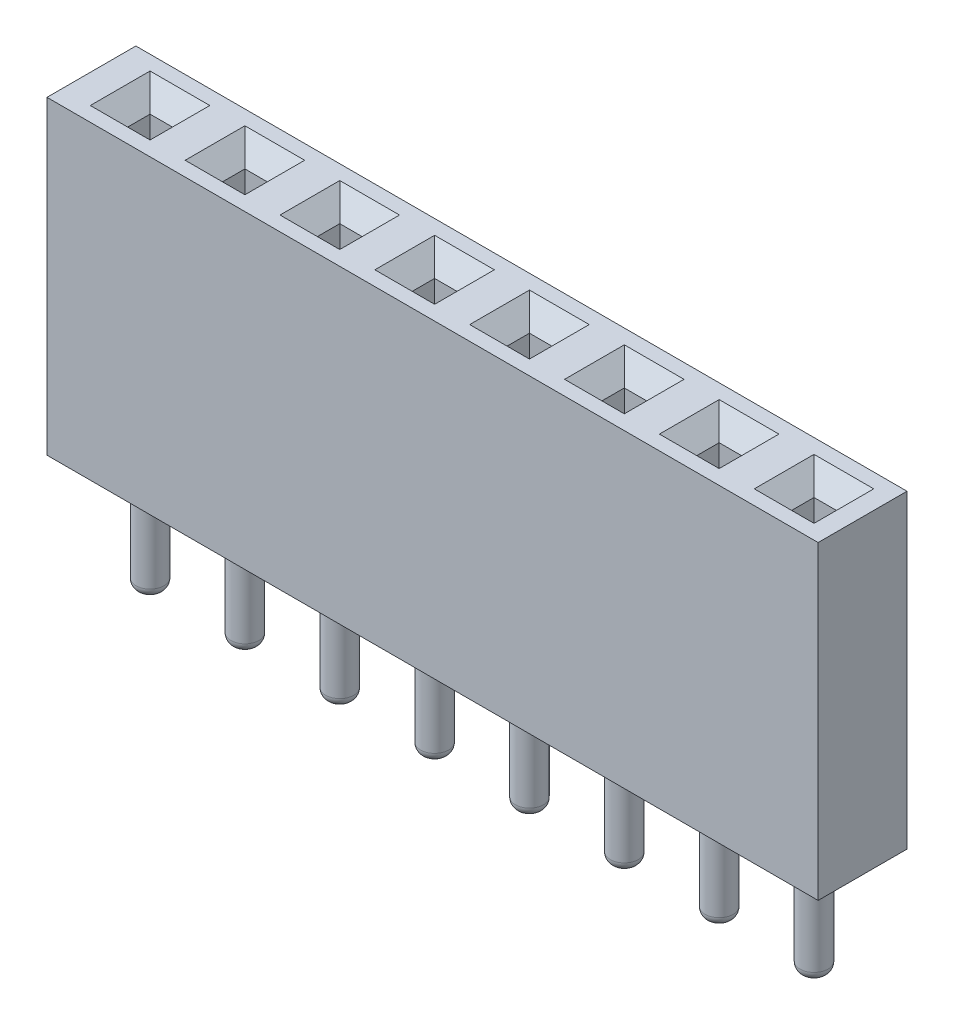
SolidWorks part; units mm, degrees
ref_plane "Front Plane" through (0, 0, 0) normal (0, 0, 1) x (1, 0, 0)
ref_plane "Top Plane" through (0, 0, 0) normal (0, 1, 0) x (1, 0, 0)
ref_plane "Right Plane" through (0, 0, 0) normal (1, 0, 0) x (0, 0, -1)
sketch "Sketch1" plane through (0, 0, 0) normal (0, 1, 0) x (1, 0, 0)
  line L1 (-10.325, -1.19) -> (10.325, -1.19)
  line L2 (-10.325, -1.19) -> (-10.325, 1.19)
  line L3 (-10.325, 1.19) -> (10.325, 1.19)
  line L4 (10.325, -1.19) -> (10.325, 1.19)
  line L5 (-10.325, -1.19) -> (10.325, 1.19) construction
  line L6 (-10.325, 1.19) -> (10.325, -1.19) construction
  point P0 (0, 0)
  dimension "D1" = 2.38
  dimension "D2" = 20.65
extrude "Boss-Extrude1" add sketch "Sketch1" along normal blind 8.3
sketch "Sketch2" plane through (0, 8.3, 0) normal (0, 1, 0) x (1, 0, 0)
  line L0 (-10.325, 0) -> (10.325, 0) construction
  line L1 (-10.325, 1.19) -> (-10.325, -1.19) construction
  line L2 (10.325, -1.19) -> (10.325, 1.19) construction
  line L4 (-9.055, -0.3) -> (-8.455, -0.3)
  line L5 (-9.055, -0.3) -> (-9.055, 0.3)
  line L6 (-9.055, 0.3) -> (-8.455, 0.3)
  line L7 (-8.455, -0.3) -> (-8.455, 0.3)
  line L8 (-9.055, -0.3) -> (-8.455, 0.3) construction
  line L9 (-9.055, 0.3) -> (-8.455, -0.3) construction
  point P6 (-8.755, 0)
  dimension "D1" = 0.6
  dimension "D2" = 0.6
  dimension "D3" = 1.27
extrude "Cut-Extrude1" cut sketch "Sketch2" against normal blind 8.3
chamfer "Chamfer1" distance 0.5 angle 45 4 edges at (-9.055, 8.3, 0) (-8.755, 8.3, 0.3) (-8.455, 8.3, 0) (-8.755, 8.3, -0.3)
sketch "Sketch3" plane through (0, 0, 0) normal (0, -1, 0) x (1, 0, 0)
  line L0 (-9.055, 0.3) -> (-8.455, 0.3) construction
  line L1 (-8.455, 0.3) -> (-8.455, -0.3) construction
  line L2 (-8.455, -0.3) -> (-9.055, -0.3) construction
  line L3 (-9.055, -0.3) -> (-9.055, 0.3) construction
  line L4 (-9.055, 0.3) -> (-8.455, 0.3) construction
  line L5 (-8.455, 0.3) -> (-8.455, -0.3) construction
  line L6 (-8.455, -0.3) -> (-9.055, -0.3) construction
  line L7 (-9.055, -0.3) -> (-9.055, 0.3) construction
  circle A0 centre (-8.755, 0) radius 0.375
  dimension "D1" = 0.75
extrude "Boss-Extrude2" add sketch "Sketch3" along normal blind 2.9
sketch "Sketch4" plane through (0, 0, 0) normal (0, 1, 0) x (1, 0, 0)
  line L0 (-8.455, 0.3) -> (-9.055, 0.3) construction
  line L1 (-8.455, -0.3) -> (-8.455, 0.3) construction
  line L2 (-9.055, -0.3) -> (-8.455, -0.3) construction
  line L3 (-9.055, 0.3) -> (-9.055, -0.3) construction
  line L4 (-8.455, -0.225) -> (-8.455, 0.225)
  line L5 (-8.53, 0.3) -> (-8.98, 0.3)
  line L6 (-9.055, 0.225) -> (-9.055, -0.225)
  line L7 (-8.98, -0.3) -> (-8.53, -0.3)
  line L8 (-8.455, -0.225) -> (-8.455, 0.225)
  line L9 (-8.53, 0.3) -> (-8.98, 0.3)
  line L10 (-9.055, 0.225) -> (-9.055, -0.225)
  line L11 (-8.98, -0.3) -> (-8.53, -0.3)
  line L12 (-8.455, 0.3) -> (-9.055, 0.3)
  line L13 (-8.455, -0.3) -> (-8.455, 0.3)
  line L14 (-9.055, -0.3) -> (-8.455, -0.3)
  line L15 (-9.055, 0.3) -> (-9.055, -0.3)
  arc A4 (-8.53, -0.3) -> (-8.455, -0.225) centre (-8.755, 0) ccw
  arc A5 (-8.455, 0.225) -> (-8.53, 0.3) centre (-8.755, 0) ccw
  arc A6 (-8.98, 0.3) -> (-9.055, 0.225) centre (-8.755, 0) ccw
  arc A7 (-9.055, -0.225) -> (-8.98, -0.3) centre (-8.755, 0) ccw
  arc A8 (-8.53, -0.3) -> (-8.455, -0.225) centre (-8.755, 0) ccw
  arc A9 (-8.455, 0.225) -> (-8.53, 0.3) centre (-8.755, 0) ccw
  arc A10 (-8.98, 0.3) -> (-9.055, 0.225) centre (-8.755, 0) ccw
  arc A11 (-9.055, -0.225) -> (-8.98, -0.3) centre (-8.755, 0) ccw
  arc M9 (-8.53, -0.3) -> (-8.455, -0.225) centre (-8.755, 0) ccw
  arc M13 (-8.98, 0.3) -> (-9.055, 0.225) centre (-8.755, 0) ccw
  dimension "D1" = 0
extrude "Boss-Extrude3" add sketch "Sketch4" along normal blind 1 contours L12 L15 M13 | L14 L13 M9
fillet "Fillet1" radius 0.25 1 edges at (-8.755, -2.9, -0.375)
pattern_linear "LPattern1" count 8 spacing 2.54 along (1, 0, 0) of "Cut-Extrude1", "Chamfer1", "Boss-Extrude2", "Boss-Extrude3", "Fillet1"
sketch "Sketch5" plane through (0, 8.3, 0) normal (0, 1, 0) x (1, 0, 0)
  circle A0 centre (-8.755, 0) radius 0.8
  circle A1 centre (-6.215, 0) radius 0.8
  circle A2 centre (9.025, 0) radius 0.8
  circle A3 centre (6.485, 0) radius 0.8
